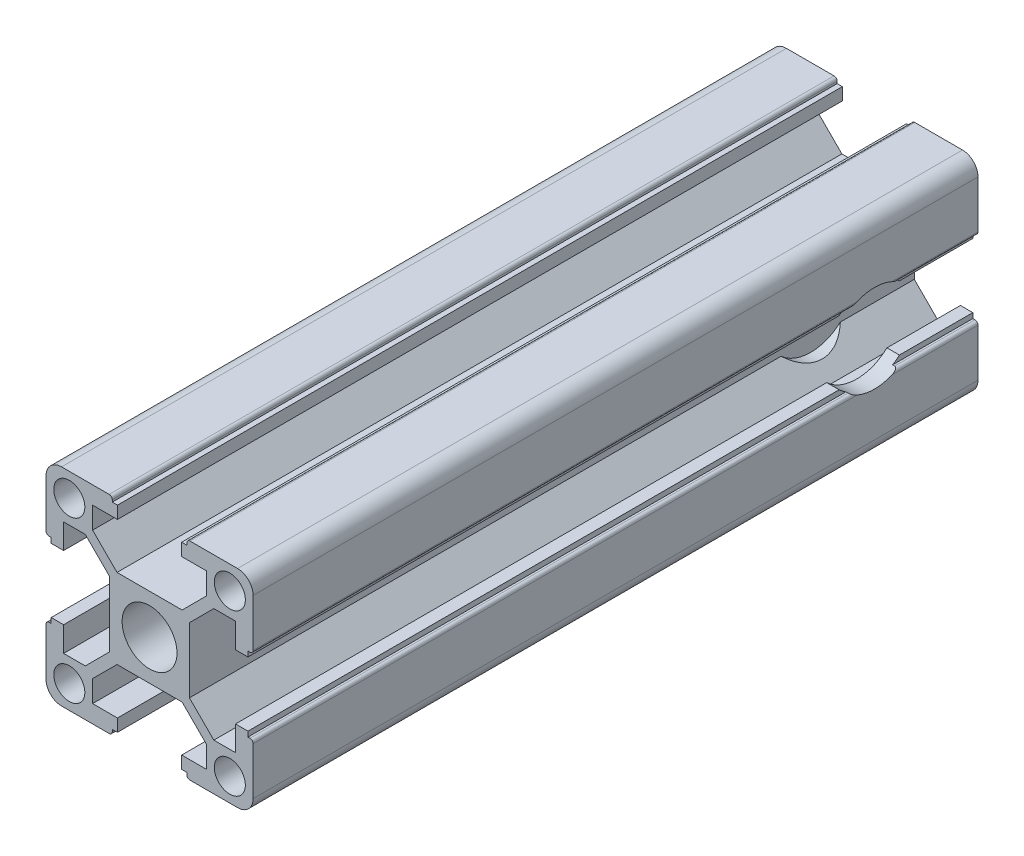
SolidWorks part; units mm, degrees
ref_plane "前视基准面" through (0, 0, 0) normal (0, 0, 1) x (1, 0, 0)
ref_plane "上视基准面" through (0, 0, 0) normal (0, 1, 0) x (1, 0, 0)
ref_plane "右视基准面" through (0, 0, 0) normal (1, 0, 0) x (0, 0, -1)
sketch "草图1" plane through (0, 0, 0) normal (0, 0, 1) x (1, 0, 0)
  line L0 (-7.75, 0) -> (0, 0) construction
  line L1 (7.75, -7.75) -> (-7.75, -7.75) construction
  line L2 (7.75, -7.75) -> (7.75, 7.75) construction
  line L3 (7.75, 7.75) -> (-7.75, 7.75) construction
  line L4 (-7.75, -7.75) -> (-7.75, 7.75) construction
  line L5 (7.75, -7.75) -> (-7.75, 7.75) construction
  line L6 (7.75, 7.75) -> (-7.75, -7.75) construction
  line L7 (0, 0) -> (0, 7.75) construction
  line L8 (3.1429, 3.85) -> (-3.1429, 3.85)
  line L9 (-3.1429, 3.85) -> (-5.5, 6.2071)
  line L10 (-5.5, 6.2071) -> (-5.5, 8.3)
  line L11 (-5.5, 8.3) -> (-3.1, 8.3)
  line L12 (-3.1, 8.3) -> (-3.1, 9.5)
  line L13 (-3.1, 9.5) -> (-3.6, 9.5)
  line L14 (-3.6, 9.5) -> (-3.6, 9.7)
  line L15 (-3.9, 10) -> (-8.5, 10)
  line L16 (-3.85, -3.1429) -> (-3.85, 3.1429)
  line L17 (-3.85, 3.1429) -> (-6.2071, 5.5)
  line L18 (-6.2071, 5.5) -> (-8.3, 5.5)
  line L19 (-8.3, 5.5) -> (-8.3, 3.1)
  line L20 (-9.5, 3.1) -> (-9.5, 3.6)
  line L21 (-8.3, 3.1) -> (-9.5, 3.1)
  line L22 (-9.5, 3.6) -> (-9.7, 3.6)
  line L23 (-10, 3.9) -> (-10, 8.5)
  line L24 (5.5, 8.3) -> (3.1, 8.3)
  line L25 (3.6, 9.5) -> (3.6, 9.7)
  line L26 (3.1, 9.5) -> (3.6, 9.5)
  line L27 (3.1, 8.3) -> (3.1, 9.5)
  line L28 (5.5, 6.2071) -> (5.5, 8.3)
  line L29 (3.1429, 3.85) -> (5.5, 6.2071)
  line L30 (3.85, -3.1429) -> (3.85, 3.1429)
  line L31 (3.85, 3.1429) -> (6.2071, 5.5)
  line L32 (9.5, 3.6) -> (9.7, 3.6)
  line L33 (8.3, 3.1) -> (9.5, 3.1)
  line L34 (9.5, 3.1) -> (9.5, 3.6)
  line L35 (8.3, 5.5) -> (8.3, 3.1)
  line L36 (6.2071, 5.5) -> (8.3, 5.5)
  line L37 (10, 3.9) -> (10, 8.5)
  line L38 (3.9, 10) -> (8.5, 10)
  line L39 (-9.5, -3.6) -> (-9.7, -3.6)
  line L40 (-8.3, -3.1) -> (-9.5, -3.1)
  line L41 (-9.5, -3.1) -> (-9.5, -3.6)
  line L42 (-8.3, -5.5) -> (-8.3, -3.1)
  line L43 (-6.2071, -5.5) -> (-8.3, -5.5)
  line L44 (-3.85, -3.1429) -> (-6.2071, -5.5)
  line L45 (-3.1429, -3.85) -> (-5.5, -6.2071)
  line L46 (-5.5, -6.2071) -> (-5.5, -8.3)
  line L47 (-3.6, -9.5) -> (-3.6, -9.7)
  line L48 (-3.1, -9.5) -> (-3.6, -9.5)
  line L49 (-3.1, -8.3) -> (-3.1, -9.5)
  line L50 (-5.5, -8.3) -> (-3.1, -8.3)
  line L51 (5.5, -6.2071) -> (5.5, -8.3)
  line L52 (3.1, -8.3) -> (3.1, -9.5)
  line L53 (3.1, -9.5) -> (3.6, -9.5)
  line L54 (3.6, -9.5) -> (3.6, -9.7)
  line L55 (5.5, -8.3) -> (3.1, -8.3)
  line L56 (3.1429, -3.85) -> (5.5, -6.2071)
  line L57 (3.1429, -3.85) -> (-3.1429, -3.85)
  line L58 (3.85, -3.1429) -> (6.2071, -5.5)
  line L59 (6.2071, -5.5) -> (8.3, -5.5)
  line L60 (8.3, -5.5) -> (8.3, -3.1)
  line L61 (9.5, -3.1) -> (9.5, -3.6)
  line L62 (8.3, -3.1) -> (9.5, -3.1)
  line L63 (9.5, -3.6) -> (9.7, -3.6)
  line L64 (3.9, -10) -> (8.5, -10)
  line L65 (10, -3.9) -> (10, -8.5)
  line L66 (-10, -3.9) -> (-10, -8.5)
  line L67 (-3.9, -10) -> (-8.5, -10)
  circle A0 centre (0, 0) radius 2.65
  circle A1 centre (-7.75, 7.75) radius 1.5
  circle A2 centre (7.75, 7.75) radius 1.5
  circle A3 centre (7.75, -7.75) radius 1.5
  circle A4 centre (-7.75, -7.75) radius 1.5
  arc A5 (-10, -8.5) -> (-8.5, -10) centre (-8.5, -8.5) ccw
  arc A6 (8.5, -10) -> (10, -8.5) centre (8.5, -8.5) ccw
  arc A7 (10, 8.5) -> (8.5, 10) centre (8.5, 8.5) ccw
  arc A8 (-8.5, 10) -> (-10, 8.5) centre (-8.5, 8.5) ccw
  arc A9 (3.6, -9.7) -> (3.9, -10) centre (3.9, -9.7) ccw
  arc A10 (-3.6, -9.7) -> (-3.9, -10) centre (-3.9, -9.7) cw
  arc A11 (-9.7, -3.6) -> (-10, -3.9) centre (-9.7, -3.9) ccw
  arc A12 (9.7, -3.6) -> (10, -3.9) centre (9.7, -3.9) cw
  arc A13 (9.7, 3.6) -> (10, 3.9) centre (9.7, 3.9) ccw
  arc A14 (-9.7, 3.6) -> (-10, 3.9) centre (-9.7, 3.9) cw
  arc A15 (3.6, 9.7) -> (3.9, 10) centre (3.9, 9.7) cw
  arc A16 (-3.6, 9.7) -> (-3.9, 10) centre (-3.9, 9.7) ccw
  point P46 (0, 3.85)
  point P56 (-3.85, 0)
  point P78 (3.85, 0)
  point P87 (-10, -10)
  point P90 (10, -10)
  point P93 (10, 10)
  point P96 (-10, 10)
  point P99 (3.6, -10)
  point P102 (-3.6, -10)
  point P105 (-10, -3.6)
  point P108 (10, -3.6)
  point P111 (10, 3.6)
  point P114 (-10, 3.6)
  point P117 (3.6, 10)
  point P120 (-3.6, 10)
  dimension "D1" = 5.3
  dimension "D2" = 3
  dimension "D11" = 1.5
  dimension "D12" = 2.25
  dimension "D13" = 0.3
  dimension "D3" = 7.7
  dimension "D4" = 6.2
  dimension "D5" = 1.7
  dimension "D6" = 1.2
  dimension "D7" = 20
  dimension "D8" = 7.2
  dimension "D9" = 11
  dimension "D10" = 1
extrude "凸台-拉伸1" add sketch "草图1" along normal mid plane 70
sketch "草图3" plane through (0, 0, 0) normal (0, 1, 0) x (1, 0, 0)
  line L0 (-3.1429, 35) -> (3.1429, 35) construction
  circle A0 centre (0, -13) radius 2
  dimension "D1" = 48
  dimension "D2" = 4
extrude "切除-拉伸1" cut sketch "草图3" against normal through all both and the other way through all
sketch "草图4" plane through (0, -3.85, 0) normal (0, -1, 0) x (1, 0, 0)
  circle A0 centre (0, 13) radius 4.25
  dimension "D1" = 8.5
extrude "切除-拉伸2" cut sketch "草图4" along normal through all contours A0
sketch "草图5" plane through (0, 0, 0) normal (1, 0, 0) x (0, 0, -1)
  line L0 (35, 3.1429) -> (35, -3.1429) construction
  circle A0 centre (25, 0) radius 2
  dimension "D1" = 4
  dimension "D2" = 10
extrude "切除-拉伸3" cut sketch "草图5" against normal through all both and the other way through all
sketch "草图6" plane through (3.85, 0, 0) normal (-1, 0, 0) x (0, 0, 1)
  circle A0 centre (-25, 0) radius 4.25
  dimension "D1" = 8.5
extrude "切除-拉伸4" cut sketch "草图6" against normal through all
